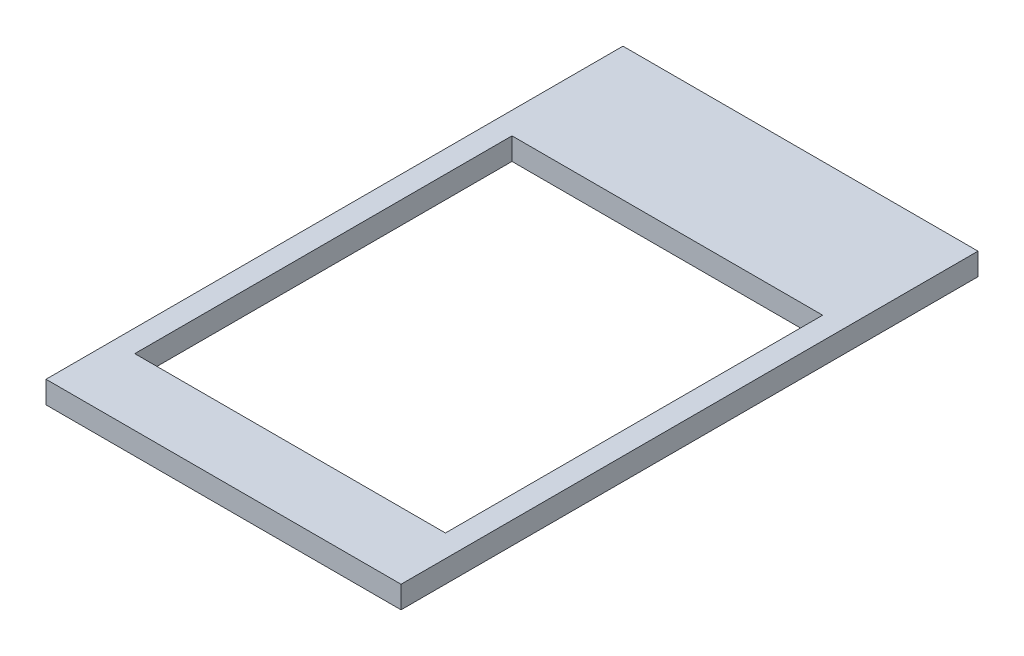
SolidWorks part; units mm, degrees
ref_plane "정면" through (0, 0, 0) normal (0, 0, 1) x (1, 0, 0)
ref_plane "윗면" through (0, 0, 0) normal (0, 1, 0) x (1, 0, 0)
ref_plane "우측면" through (0, 0, 0) normal (1, 0, 0) x (0, 0, -1)
sketch "스케치1" plane through (0, 0, 0) normal (0, 1, 0) x (1, 0, 0)
  line L1 (8, -13) -> (-8, -13)
  line L2 (8, -13) -> (8, 13)
  line L3 (8, 13) -> (-8, 13)
  line L4 (-8, -13) -> (-8, 13)
  line L5 (8, -13) -> (-8, 13) construction
  line L6 (8, 13) -> (-8, -13) construction
  point P0 (0, 0)
  dimension "D1" = 16
  dimension "D2" = 26
extrude "보스-돌출1" add sketch "스케치1" along normal blind 5
sketch "스케치2" plane through (0, 0, 0) normal (0, 1, 0) x (1, 0, 0)
  line L0 (-8, 13) -> (-8, -13) construction
  line L1 (-7, 13) -> (7, 13)
  line L2 (-7, 13) -> (-7, -12)
  line L3 (-7, -12) -> (7, -12)
  line L4 (7, 13) -> (7, -12)
  line L6 (8, 13) -> (-8, 13) construction
  dimension "D1" = 14
  dimension "D2" = 25
  dimension "D3" = 1
extrude "컷-돌출1" cut sketch "스케치2" along normal blind 10 from offset 1
sketch "스케치3" plane through (0, 0, 0) normal (0, 1, 0) x (1, 0, 0)
  line L1 (8, -13) -> (-8, -13)
  line L2 (8, -13) -> (8, 13)
  line L3 (8, 13) -> (-8, 13)
  line L4 (-8, -13) -> (-8, 13)
  line L5 (8, -13) -> (-8, 13) construction
  line L6 (8, 13) -> (-8, -13) construction
  point P0 (0, 0)
extrude "보스-돌출3" add sketch "스케치3" along normal blind 1 from offset 5 separate body
sketch "스케치4" plane through (0, 0, 0) normal (0, 1, 0) x (1, 0, 0)
  line L0 (-8, -13) -> (8, -13) construction
  line L1 (-7, 7) -> (7, 7)
  line L2 (-7, 7) -> (-7, -10)
  line L3 (-7, -10) -> (7, -10)
  line L4 (7, 7) -> (7, -10)
  line L5 (8, -13) -> (8, 13) construction
  dimension "D1" = 3
  dimension "D2" = 17
  dimension "D3" = 14
  dimension "D4" = 1
extrude "컷-돌출2" cut sketch "스케치4" against normal blind 1 from surface at 6 starting at face at (0, 6, 0)
sketch "스케치6" plane through (0, 0, 0) normal (0, -1, 0) x (1, 0, 0)
  line L4 (-8, 13) -> (-8, -13)
  line L5 (-8, -13) -> (8, -13)
  line L6 (8, -13) -> (8, 13)
  line L7 (8, 13) -> (-8, 13)
  line L8 (-8, 13) -> (-8, -13)
  line L9 (-8, -13) -> (8, -13)
  line L10 (8, -13) -> (8, 13)
  line L11 (8, 13) -> (-8, 13)
  dimension "D1" = 0
extrude "컷-돌출4" cut sketch "스케치6" against normal blind 5
